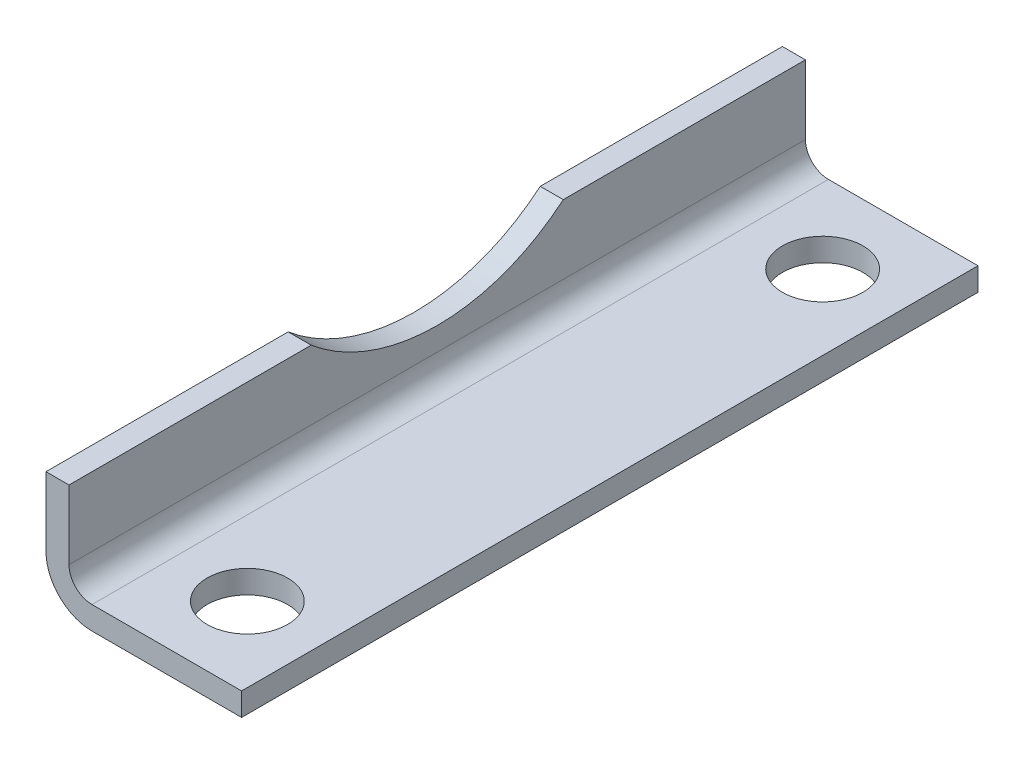
SolidWorks part; units mm, degrees
material "AISI 1010 钢，热轧条材"
ref_plane "前视基准面" through (0, 0, 0) normal (0, 0, 1) x (1, 0, 0)
ref_plane "上视基准面" through (0, 0, 0) normal (0, 1, 0) x (1, 0, 0)
ref_plane "右视基准面" through (0, 0, 0) normal (1, 0, 0) x (0, 0, -1)
sketch "草图1" plane through (0, 0, 0) normal (0, 0, 1) x (1, 0, 0)
  line L0 (0, 0) -> (0, 10)
  line L1 (0, 0) -> (17, 0)
  line L2 (17, 0) -> (17, 2)
  line L3 (17, 2) -> (2, 2)
  line L4 (2, 2) -> (2, 10)
  line L5 (2, 10) -> (0, 10)
  dimension "D1" = 17
  dimension "D2" = 10
  dimension "D3" = 2
  dimension "D4" = 2
extrude "凸台-拉伸1" add sketch "草图1" along normal mid plane 64
fillet "圆角1" radius 4 1 edges at (0, 0, 0)
fillet "圆角2" radius 2 1 edges at (2, 2, 0)
sketch "草图2" plane through (0, 0, 0) normal (0, -1, 0) x (1, 0, 0)
  line L0 (10.5, 32) -> (10.5, -32) construction
  line L1 (4, 32) -> (17, 32) construction
  line L2 (4, -32) -> (17, -32) construction
  line L3 (17, 32) -> (17, -32) construction
  line L4 (0, 0) -> (50000, 0) construction
  circle A0 centre (10.5, 25) radius 3.5
  circle A1 centre (10.5, -25) radius 3.5
  dimension "D1" = 7
  dimension "D3" = 50
  dimension "D2" = 6.5
extrude "切除-拉伸1" cut sketch "草图2" against normal blind 10
sketch "草图3" plane through (0, 0, 0) normal (-1, 0, 0) x (0, 0, 1)
  line L0 (0, 0) -> (0, 27.0193) construction
  line L1 (32, 0) -> (-32, 0) construction
  circle A0 centre (0, 23) radius 17
  dimension "D1" = 34
  dimension "D2" = 23
extrude "切除-拉伸2" cut sketch "草图3" against normal blind 10
